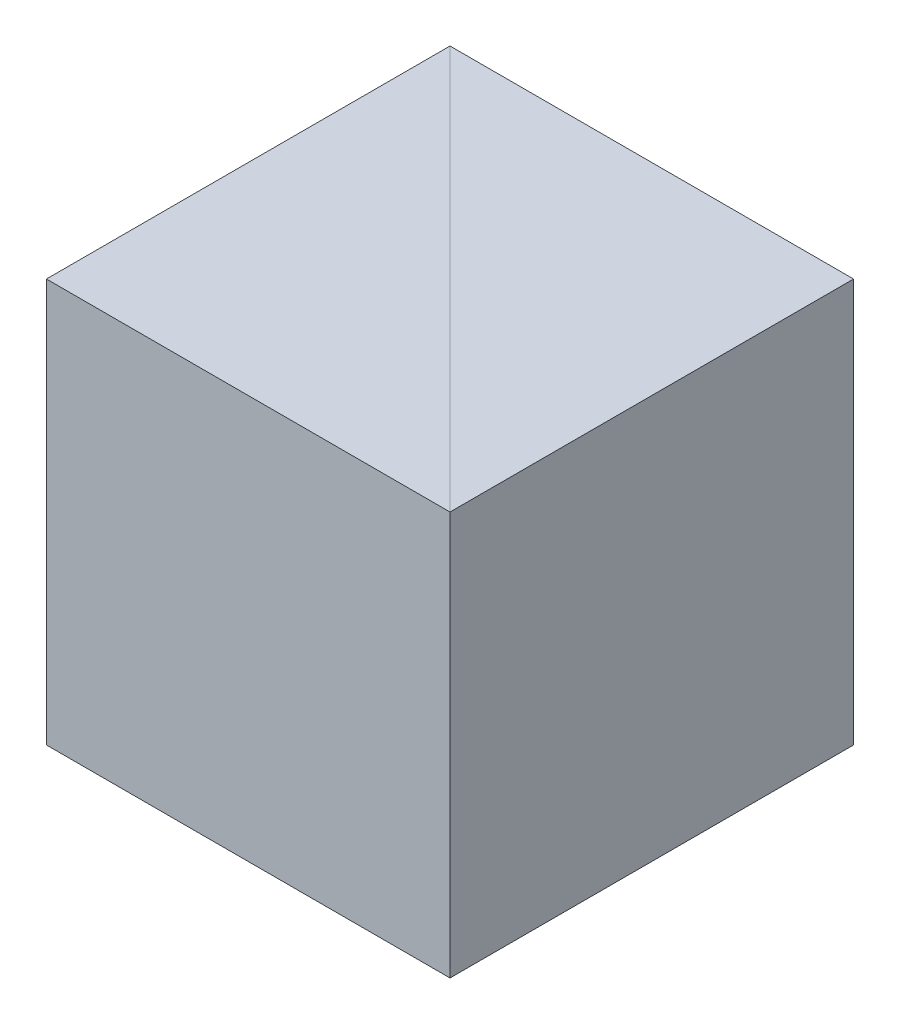
SolidWorks part; units mm, degrees
material "Acrylic (Medium-high impact)"
ref_plane "Front Plane" through (0, 0, 0) normal (0, 0, 1) x (1, 0, 0)
ref_plane "Top Plane" through (0, 0, 0) normal (0, 1, 0) x (1, 0, 0)
ref_plane "Right Plane" through (0, 0, 0) normal (1, 0, 0) x (0, 0, -1)
sketch "Sketch1" plane through (0, 0, 0) normal (0, 1, 0) x (1, 0, 0)
  line L1 (-20, -20) -> (20, -20)
  line L2 (-20, -20) -> (-20, 20)
  line L3 (-20, 20) -> (20, 20)
  line L4 (20, -20) -> (20, 20)
  line L5 (-20, -20) -> (20, 20) construction
  line L6 (-20, 20) -> (20, -20) construction
  point P0 (0, 0)
  dimension "D1" = 40
extrude "Boss-Extrude1" add sketch "Sketch1" along normal blind 40
ref_plane "Plane1" through (0, 0, 0) normal (-0.7071, 0, 0.7071) x (0.7071, 0, 0.7071)
split "Split1" trim tools "Plane1" bodies to split 101 resulting bodies 102 103
